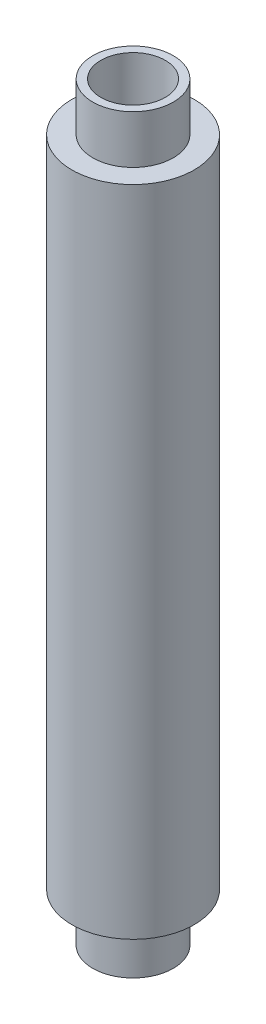
SolidWorks part; units mm, degrees
ref_plane "Front Plane" through (0, 0, 0) normal (0, 0, 1) x (1, 0, 0)
ref_plane "Top Plane" through (0, 0, 0) normal (0, 1, 0) x (1, 0, 0)
ref_plane "Right Plane" through (0, 0, 0) normal (1, 0, 0) x (0, 0, -1)
sketch "Sketch1" plane through (0, 0, 0) normal (0, 1, 0) x (1, 0, 0)
  circle A0 centre (0, 0) radius 19
  dimension "D1" = 38
extrude "Boss-Extrude1" add sketch "Sketch1" along normal blind 203
sketch "Sketch2" plane through (0, 0, 0) normal (0, -1, 0) x (1, 0, 0)
  circle A0 centre (0, 0) radius 12.5
  circle A1 centre (0, 0) radius 10
extrude "Boss-Extrude2" add sketch "Sketch2" along normal blind 15
sketch "Sketch3" plane through (0, 203, 0) normal (0, 1, 0) x (1, 0, 0)
  circle A0 centre (0, 0) radius 12.5
  circle A1 centre (0, 0) radius 10
extrude "Boss-Extrude3" add sketch "Sketch3" along normal blind 15
